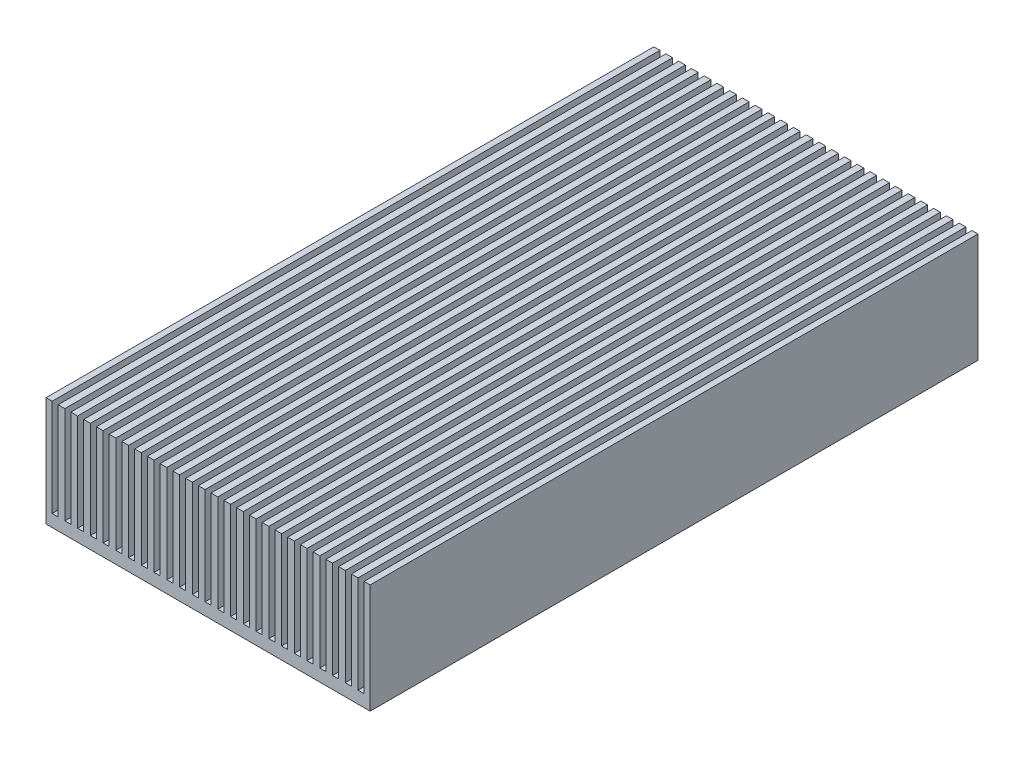
SolidWorks part; units mm, degrees
ref_plane "Front Plane" through (0, 0, 0) normal (0, 0, 1) x (1, 0, 0)
ref_plane "Top Plane" through (0, 0, 0) normal (0, 1, 0) x (1, 0, 0)
ref_plane "Right Plane" through (0, 0, 0) normal (1, 0, 0) x (0, 0, -1)
sketch "Sketch1" plane through (0, 0, 0) normal (0, 1, 0) x (1, 0, 0)
  line L1 (0, 0) -> (80, 0)
  line L2 (0, 0) -> (0, 150)
  line L3 (0, 150) -> (80, 150)
  line L4 (80, 0) -> (80, 150)
  dimension "D1" = 150
  dimension "D2" = 80
extrude "Boss-Extrude1" add sketch "Sketch1" along normal blind 27
sketch "Sketch2" plane through (0, 27, 0) normal (0, 1, 0) x (1, 0, 0)
  line L0 (0, 0) -> (80, 0) construction
  line L1 (1.5, 150) -> (3, 150)
  line L2 (1.5, 150) -> (1.5, 0)
  line L3 (1.5, 0) -> (3, 0)
  line L4 (3, 150) -> (3, 0)
  line L5 (4.6458, 150) -> (4.6458, 0)
  line L6 (4.6458, 150) -> (6.1458, 150)
  line L7 (6.1458, 150) -> (6.1458, 0)
  line L8 (4.6458, 0) -> (6.1458, 0)
  line L9 (7.7917, 150) -> (7.7917, 0)
  line L10 (7.7917, 150) -> (9.2917, 150)
  line L11 (9.2917, 150) -> (9.2917, 0)
  line L12 (7.7917, 0) -> (9.2917, 0)
  line L13 (10.9375, 150) -> (10.9375, 0)
  line L14 (10.9375, 150) -> (12.4375, 150)
  line L15 (12.4375, 150) -> (12.4375, 0)
  line L16 (10.9375, 0) -> (12.4375, 0)
  line L17 (14.0833, 150) -> (14.0833, 0)
  line L18 (14.0833, 150) -> (15.5833, 150)
  line L19 (15.5833, 150) -> (15.5833, 0)
  line L20 (14.0833, 0) -> (15.5833, 0)
  line L21 (17.2292, 150) -> (17.2292, 0)
  line L22 (17.2292, 150) -> (18.7292, 150)
  line L23 (18.7292, 150) -> (18.7292, 0)
  line L24 (17.2292, 0) -> (18.7292, 0)
  line L25 (20.375, 150) -> (20.375, 0)
  line L26 (20.375, 150) -> (21.875, 150)
  line L27 (21.875, 150) -> (21.875, 0)
  line L28 (20.375, 0) -> (21.875, 0)
  line L29 (23.5208, 150) -> (23.5208, 0)
  line L30 (23.5208, 150) -> (25.0208, 150)
  line L31 (25.0208, 150) -> (25.0208, 0)
  line L32 (23.5208, 0) -> (25.0208, 0)
  line L33 (26.6667, 150) -> (26.6667, 0)
  line L34 (26.6667, 150) -> (28.1667, 150)
  line L35 (28.1667, 150) -> (28.1667, 0)
  line L36 (26.6667, 0) -> (28.1667, 0)
  line L37 (29.8125, 150) -> (29.8125, 0)
  line L38 (29.8125, 150) -> (31.3125, 150)
  line L39 (31.3125, 150) -> (31.3125, 0)
  line L40 (29.8125, 0) -> (31.3125, 0)
  line L41 (32.9583, 150) -> (32.9583, 0)
  line L42 (32.9583, 150) -> (34.4583, 150)
  line L43 (34.4583, 150) -> (34.4583, 0)
  line L44 (32.9583, 0) -> (34.4583, 0)
  line L45 (36.1042, 150) -> (36.1042, 0)
  line L46 (36.1042, 150) -> (37.6042, 150)
  line L47 (37.6042, 150) -> (37.6042, 0)
  line L48 (36.1042, 0) -> (37.6042, 0)
  line L49 (39.25, 150) -> (39.25, 0)
  line L50 (39.25, 150) -> (40.75, 150)
  line L51 (40.75, 150) -> (40.75, 0)
  line L52 (39.25, 0) -> (40.75, 0)
  line L53 (42.3958, 150) -> (42.3958, 0)
  line L54 (42.3958, 150) -> (43.8958, 150)
  line L55 (43.8958, 150) -> (43.8958, 0)
  line L56 (42.3958, 0) -> (43.8958, 0)
  line L57 (45.5417, 150) -> (45.5417, 0)
  line L58 (45.5417, 150) -> (47.0417, 150)
  line L59 (47.0417, 150) -> (47.0417, 0)
  line L60 (45.5417, 0) -> (47.0417, 0)
  line L61 (48.6875, 150) -> (48.6875, 0)
  line L62 (48.6875, 150) -> (50.1875, 150)
  line L63 (50.1875, 150) -> (50.1875, 0)
  line L64 (48.6875, 0) -> (50.1875, 0)
  line L65 (51.8333, 150) -> (51.8333, 0)
  line L66 (51.8333, 150) -> (53.3333, 150)
  line L67 (53.3333, 150) -> (53.3333, 0)
  line L68 (51.8333, 0) -> (53.3333, 0)
  line L69 (54.9792, 150) -> (54.9792, 0)
  line L70 (54.9792, 150) -> (56.4792, 150)
  line L71 (56.4792, 150) -> (56.4792, 0)
  line L72 (54.9792, 0) -> (56.4792, 0)
  line L73 (58.125, 150) -> (58.125, 0)
  line L74 (58.125, 150) -> (59.625, 150)
  line L75 (59.625, 150) -> (59.625, 0)
  line L76 (58.125, 0) -> (59.625, 0)
  line L77 (61.2708, 150) -> (61.2708, 0)
  line L78 (61.2708, 150) -> (62.7708, 150)
  line L79 (62.7708, 150) -> (62.7708, 0)
  line L80 (61.2708, 0) -> (62.7708, 0)
  line L81 (64.4167, 150) -> (64.4167, 0)
  line L82 (64.4167, 150) -> (65.9167, 150)
  line L83 (65.9167, 150) -> (65.9167, 0)
  line L84 (64.4167, 0) -> (65.9167, 0)
  line L85 (67.5625, 150) -> (67.5625, 0)
  line L86 (67.5625, 150) -> (69.0625, 150)
  line L87 (69.0625, 150) -> (69.0625, 0)
  line L88 (67.5625, 0) -> (69.0625, 0)
  line L89 (70.7083, 150) -> (70.7083, 0)
  line L90 (70.7083, 150) -> (72.2083, 150)
  line L91 (72.2083, 150) -> (72.2083, 0)
  line L92 (70.7083, 0) -> (72.2083, 0)
  line L93 (73.8542, 150) -> (73.8542, 0)
  line L94 (73.8542, 150) -> (75.3542, 150)
  line L95 (75.3542, 150) -> (75.3542, 0)
  line L96 (73.8542, 0) -> (75.3542, 0)
  line L97 (77, 150) -> (77, 0)
  line L98 (77, 150) -> (78.5, 150)
  line L99 (78.5, 150) -> (78.5, 0)
  line L100 (77, 0) -> (78.5, 0)
  line L101 (80, 150) -> (0, 150) construction
  line L102 (78.5, 0) -> (80, 0) construction
  line L103 (1.5, 0) -> (0, 0) construction
  dimension "D1" = 1.5
  dimension "D2" = 25
extrude "Cut-Extrude1" cut sketch "Sketch2" against normal blind 24
